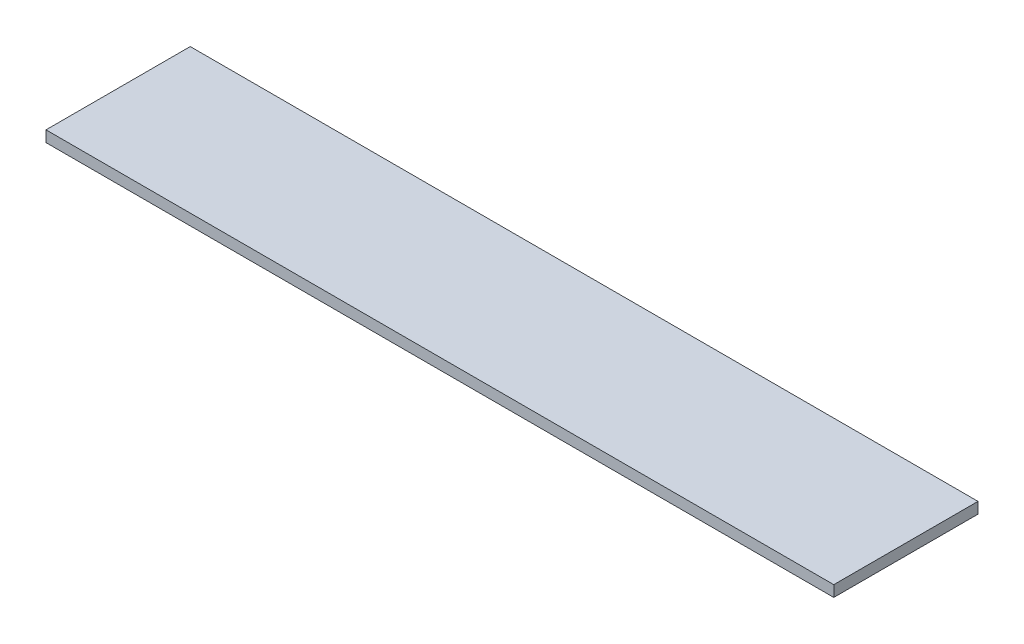
SolidWorks part; units mm, degrees
ref_plane "Front Plane" through (0, 0, 0) normal (0, 0, 1) x (1, 0, 0)
ref_plane "Top Plane" through (0, 0, 0) normal (0, 1, 0) x (1, 0, 0)
ref_plane "Right Plane" through (0, 0, 0) normal (1, 0, 0) x (0, 0, -1)
sketch "Sketch1" plane through (0, 0, 0) normal (0, 0, 1) x (1, 0, 0)
  line L1 (-28.3111, 16.1056) -> (42.6889, 16.1056)
  line L2 (-28.3111, 16.1056) -> (-28.3111, 3.1056)
  line L3 (-28.3111, 3.1056) -> (42.6889, 3.1056)
  line L4 (42.6889, 16.1056) -> (42.6889, 3.1056)
  line L5 (7.1889, 3.1056) -> (7.1889, 16.1056) construction
  line L6 (-28.3111, 9.6056) -> (42.6889, 9.6056) construction
  point P104 (7.1889, 9.6056)
  dimension "D1" = 13
  dimension "D2" = 71
extrude "Boss-Extrude1" add sketch "Sketch1" along normal blind 1
move or copy body "Body-Move/Copy1" bodies to move or copy 102 copy no rotation origin (0, 9.6056, 0.25) rotation axis (1, 0, 0) rotation angle 90
